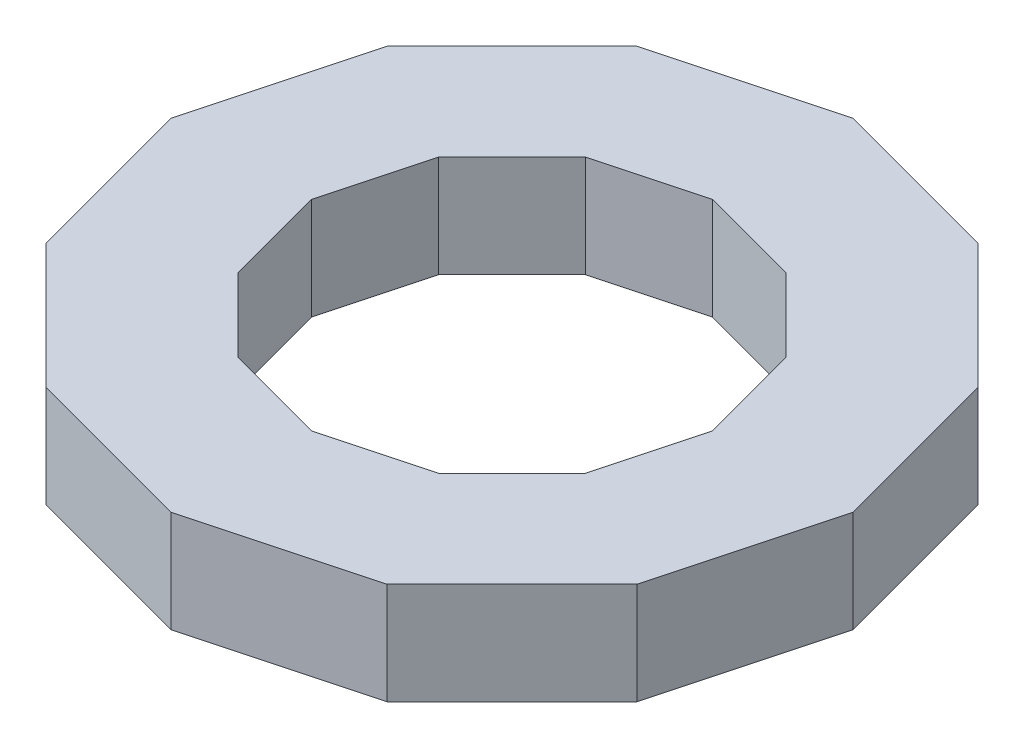
SolidWorks part; units mm, degrees
ref_plane "Front Plane" through (0, 0, 0) normal (0, 0, 1) x (1, 0, 0)
ref_plane "Top Plane" through (0, 0, 0) normal (0, 1, 0) x (1, 0, 0)
ref_plane "Right Plane" through (0, 0, 0) normal (1, 0, 0) x (0, 0, -1)
sketch "Sketch1" plane through (0, 0, 0) normal (0, 1, 0) x (1, 0, 0)
  line L0 (0, 0) -> (37.4937, 0) construction
  line L1 (37.4937, 0) -> (32.4705, 18.7469)
  line L2 (32.4705, 18.7469) -> (18.7469, 32.4705)
  line L3 (18.7469, 32.4705) -> (0, 37.4937)
  line L4 (0, 37.4937) -> (-18.7469, 32.4705)
  line L5 (-18.7469, 32.4705) -> (-32.4705, 18.7469)
  line L6 (-32.4705, 18.7469) -> (-37.4937, 0)
  line L7 (-37.4937, 0) -> (-32.4705, -18.7469)
  line L8 (-32.4705, -18.7469) -> (-18.7469, -32.4705)
  line L9 (-18.7469, -32.4705) -> (0, -37.4937)
  line L10 (0, -37.4937) -> (18.7469, -32.4705)
  line L11 (18.7469, -32.4705) -> (32.4705, -18.7469)
  line L12 (32.4705, -18.7469) -> (37.4937, 0)
  line L13 (63.7897, 0) -> (55.2435, 31.8949)
  line L14 (55.2435, 31.8949) -> (31.8949, 55.2435)
  line L15 (31.8949, 55.2435) -> (0, 63.7897)
  line L16 (0, 63.7897) -> (-31.8949, 55.2435)
  line L17 (-31.8949, 55.2435) -> (-55.2435, 31.8949)
  line L18 (-55.2435, 31.8949) -> (-63.7897, 0)
  line L19 (-63.7897, 0) -> (-55.2435, -31.8949)
  line L20 (-55.2435, -31.8949) -> (-31.8949, -55.2435)
  line L21 (-31.8949, -55.2435) -> (0, -63.7897)
  line L22 (0, -63.7897) -> (31.8949, -55.2435)
  line L23 (31.8949, -55.2435) -> (55.2435, -31.8949)
  line L24 (55.2435, -31.8949) -> (63.7897, 0)
  line L25 (55.2435, 31.8949) -> (32.4705, 18.7469) construction
  circle A0 centre (0, 0) radius 36.2162 construction
  circle A1 centre (0, 0) radius 61.6162 construction
  dimension "D1" = 25.4
  dimension "D2" = 33.02
  dimension "D3" = 105
  dimension "D4" = 61.6162
extrude "Boss-Extrude1" add sketch "Sketch1" along normal blind 19.05
